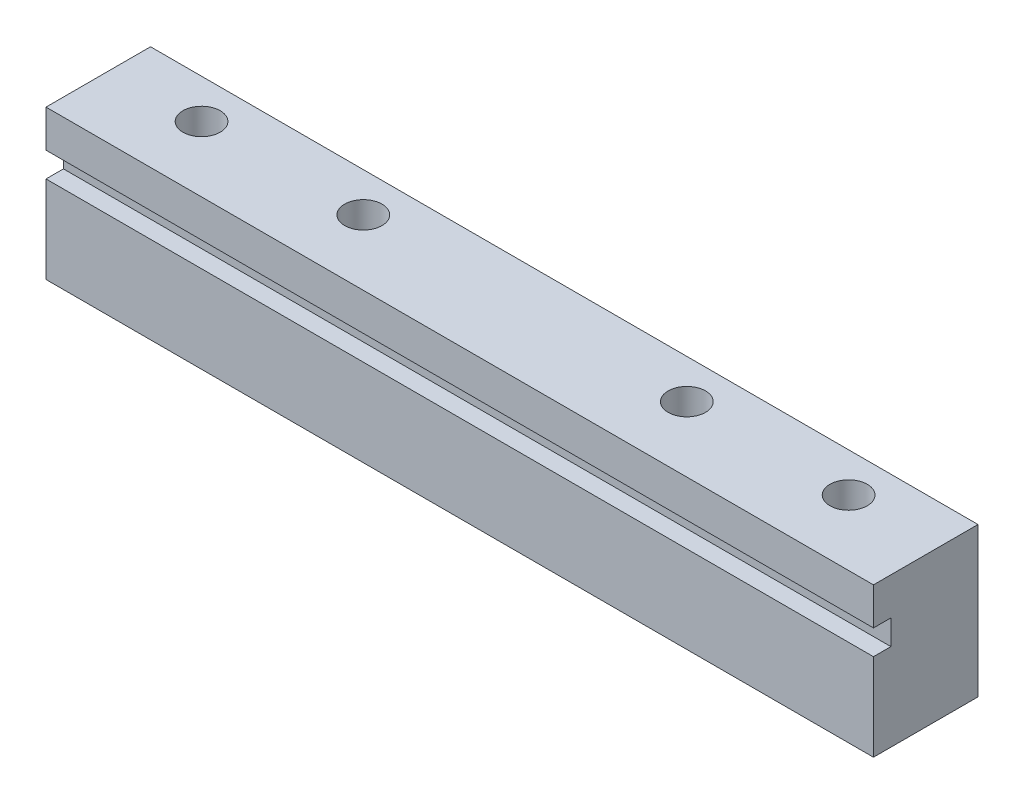
SolidWorks part; units mm, degrees
ref_plane "前视基准面" through (0, 0, 0) normal (0, 0, 1) x (1, 0, 0)
ref_plane "上视基准面" through (0, 0, 0) normal (0, 1, 0) x (1, 0, 0)
ref_plane "右视基准面" through (0, 0, 0) normal (1, 0, 0) x (0, 0, -1)
sketch "草图1" plane through (0, 0, 0) normal (0, 1, 0) x (1, 0, 0)
  line L1 (-33.25, 4.2) -> (33.25, 4.2)
  line L2 (-33.25, 4.2) -> (-33.25, -4.2)
  line L3 (-33.25, -4.2) -> (33.25, -4.2)
  line L4 (33.25, 4.2) -> (33.25, -4.2)
  line L5 (-33.25, 4.2) -> (33.25, -4.2) construction
  line L6 (-33.25, -4.2) -> (33.25, 4.2) construction
  point P0 (0, 0)
  dimension "D1" = 8.4
  dimension "D2" = 66.5
extrude "凸台-拉伸1" add sketch "草图1" along normal blind 12
sketch "草图2" plane through (33.25, 0, 0) normal (1, 0, 0) x (0, 0, -1)
  line L0 (-4.2, 12) -> (-4.2, 0) construction
  line L1 (-4.2, 9) -> (-2.8, 9)
  line L2 (-4.2, 9) -> (-4.2, 7)
  line L3 (-4.2, 7) -> (-2.8, 7)
  line L4 (-2.8, 9) -> (-2.8, 7)
  line L5 (-4.2, 12) -> (4.2, 12) construction
  line L8 (4.2, 12) -> (4.2, 0) construction
  dimension "D1" = 3
  dimension "D2" = 5
  dimension "D3" = 7
extrude "切除-拉伸1" cut sketch "草图2" against normal blind 104
ref_plane "基准面1" through (0, 0, 0) normal (1, 0, 0) x (0, 0, -1)
sketch "草图4" plane through (0, 0, 0) normal (0, -1, 0) x (1, 0, 0)
  circle A4 centre (-26, -1.05) radius 1.5
  circle A5 centre (-13, -1.05) radius 1.5
  circle A6 centre (26, -1.05) radius 1.5
  circle A7 centre (13, -1.05) radius 1.5
extrude "切除-拉伸3" cut sketch "草图4" against normal through all
